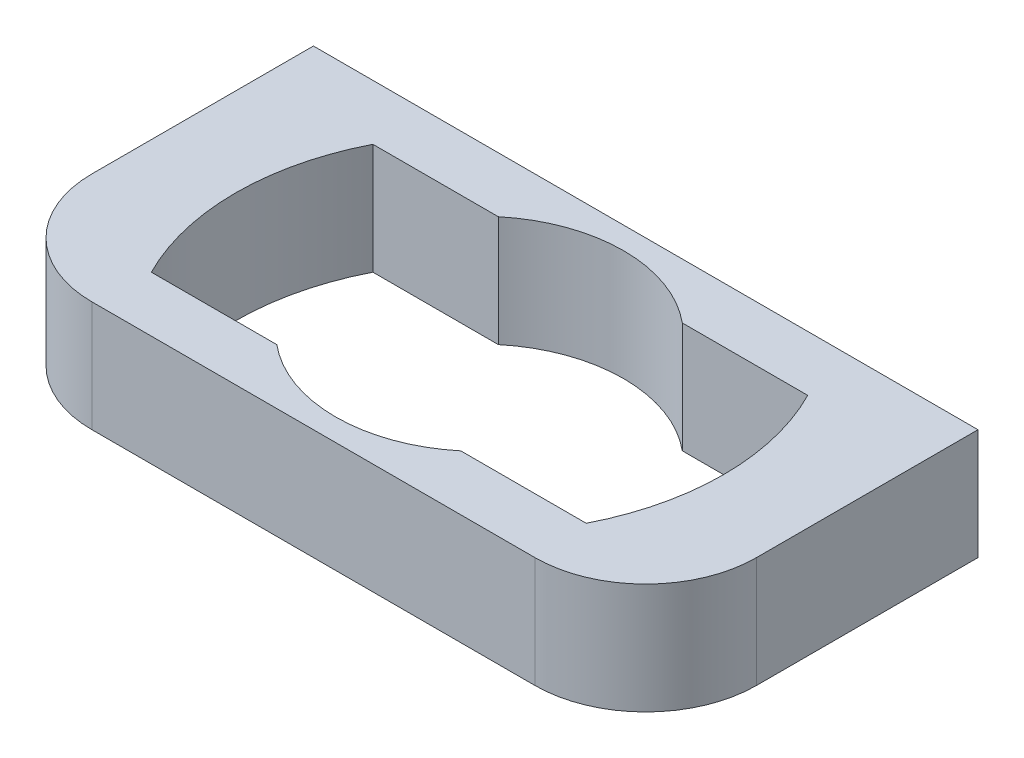
SolidWorks part; units mm, degrees
ref_plane "正面" through (0, 0, 0) normal (0, 0, 1) x (1, 0, 0)
ref_plane "平面" through (0, 0, 0) normal (0, 1, 0) x (1, 0, 0)
ref_plane "右側面" through (0, 0, 0) normal (1, 0, 0) x (0, 0, -1)
sketch "ｽｹｯﾁ1" plane through (0, 0, 0) normal (0, 1, 0) x (1, 0, 0)
  line L0 (-25.8461, 0) -> (29.9033, 0) construction
  line L1 (0, 18.6332) -> (0, -16.2289) construction
  line L3 (-30, 10) -> (30, 10)
  line L4 (-30, 10) -> (-30, -10)
  line L5 (-30, -10) -> (30, -10)
  line L6 (30, 10) -> (30, -10)
  line L7 (-30, 10) -> (30, -10) construction
  line L8 (-30, -10) -> (30, 10) construction
  line L9 (-30, 10) -> (30, 10)
  line L10 (-30, 10) -> (-30, 15)
  line L11 (-30, 15) -> (30, 15)
  line L12 (30, 10) -> (30, 15)
  line L13 (-30, -10) -> (30, -10)
  line L14 (-30, -10) -> (-30, -15)
  line L15 (-30, -15) -> (30, -15)
  line L16 (30, -10) -> (30, -15)
  arc A0 (19.6296, -10) -> (19.6296, 10) centre (0, 0) ccw
  arc A1 (-19.6296, 10) -> (-19.6296, -10) centre (0, 0) ccw
  circle A2 centre (0, 0) radius 13
  dimension "D1" = 22.03
  dimension "D2" = 22.03
  dimension "D6" = 26
  dimension "D3" = 60
  dimension "D4" = 20
  dimension "D5" = 15
  dimension "D7" = 5
extrude "ﾎﾞｽ - 押し出し1" add sketch "ｽｹｯﾁ1" along normal blind 10 contours A1 L3 L4 L5 | A0 L5 L6 L9 | A2 L9 L12 L11 L10 L3 | A2 L13 L5 L14 L15 L16
fillet "ﾌｨﾚｯﾄ1" radius 10 2 edges at (-30, 5, 15) (30, 5, 15)
sketch "ｽｹｯﾁ2" plane through (0, 0, -15) normal (0, 0, -1) x (-1, 0, 0)
  line L0 (0, 0) -> (0, 10) construction
  line L1 (30, 10) -> (-30, 10) construction
  line L2 (30, 5) -> (-30, 5) construction
  line L3 (30, 10) -> (30, 0) construction
  line L4 (-30, 10) -> (-30, 0) construction
  circle A0 centre (25, 5) radius 2.4
  circle A1 centre (-25, 5) radius 2.4
  dimension "D1" = 4.8
  dimension "D2" = 25
  dimension "D3" = 25
extrude "ｶｯﾄ - 押し出し1" cut sketch "ｽｹｯﾁ2" against normal blind 6
